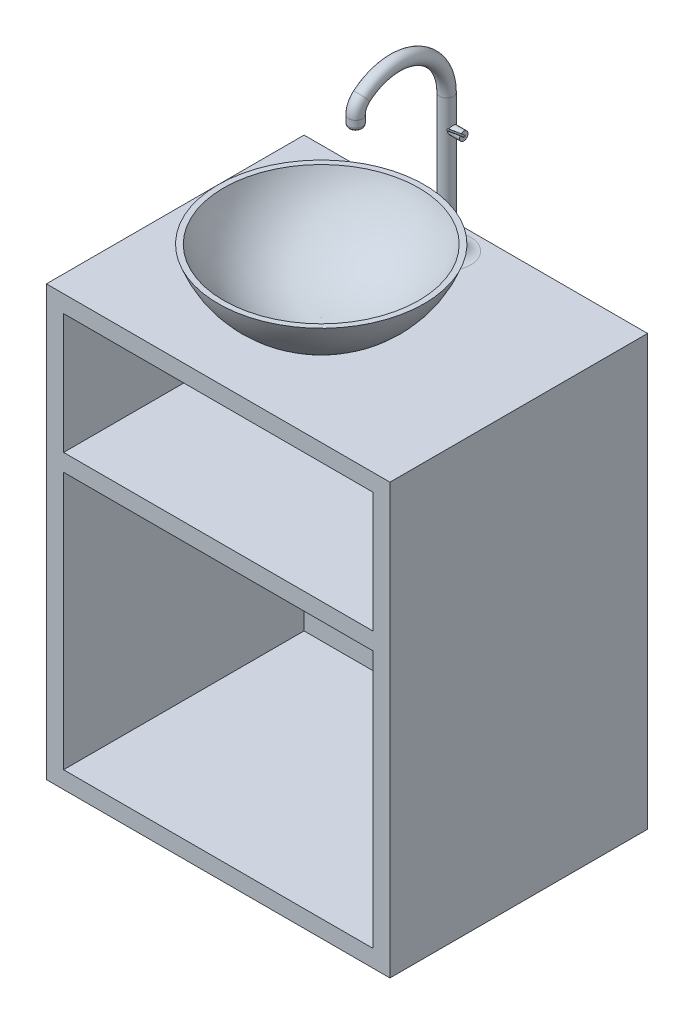
SolidWorks part; units mm, degrees
ref_plane "前基準面" through (0, 0, 0) normal (0, 0, 1) x (1, 0, 0)
ref_plane "上基準面" through (0, 0, 0) normal (0, 1, 0) x (1, 0, 0)
ref_plane "右基準面" through (0, 0, 0) normal (1, 0, 0) x (0, 0, -1)
sketch "草圖1" plane through (0, 0, 0) normal (0, 0, 1) x (1, 0, 0)
  line L1 (-10, 12.5) -> (10, 12.5)
  line L2 (-10, 12.5) -> (-10, -12.5)
  line L3 (-10, -12.5) -> (10, -12.5)
  line L4 (10, 12.5) -> (10, -12.5)
  line L5 (-10, 12.5) -> (10, -12.5) construction
  line L6 (-10, -12.5) -> (10, 12.5) construction
  point P0 (0, 0)
  dimension "D1" = 25
  dimension "D2" = 20
extrude "填料-伸長1" add sketch "草圖1" along normal blind 15
sketch "草圖2" plane through (0, 0, 15) normal (0, 0, 1) x (1, 0, 0)
  line L0 (0, -12.5) -> (0, 12.5) construction
  line L1 (-10, -12.5) -> (10, -12.5) construction
  line L2 (10, 12.5) -> (-10, 12.5) construction
  line L3 (10, -12.5) -> (10, 12.5) construction
  line L4 (-9, 11.5) -> (9, 11.5)
  line L5 (-9, 11.5) -> (-9, 4.5)
  line L6 (-9, 4.5) -> (9, 4.5)
  line L7 (9, 11.5) -> (9, 4.5)
  line L8 (-9, 11.5) -> (9, 4.5) construction
  line L9 (-9, 4.5) -> (9, 11.5) construction
  line L10 (-9, 3.5) -> (9, 3.5)
  line L11 (-9, 3.5) -> (-9, -11.5)
  line L12 (-9, -11.5) -> (9, -11.5)
  line L13 (9, 3.5) -> (9, -11.5)
  line L14 (-9, 3.5) -> (9, -11.5) construction
  line L15 (-9, -11.5) -> (9, 3.5) construction
  point P6 (0, 8)
  point P11 (0, -4)
  dimension "D1" = 1
  dimension "D2" = 1
  dimension "D3" = 1
  dimension "D4" = 1
  dimension "D5" = 1
  dimension "D6" = 15
extrude "除料-伸長1" cut sketch "草圖2" against normal blind 14
ref_plane "平面1" through (0, 0, 0) normal (1, 0, 0) x (0, 0, -1)
sketch "草圖4" plane through (0, 0, 0) normal (1, 0, 0) x (0, 0, -1)
  line L0 (-9, -12.5) -> (-9, 31.1641) construction
  line L1 (-15, -12.5) -> (0, -12.5) construction
  line L2 (-15, -12.5) -> (-15, 12.5) construction
  line L3 (-26.1513, 16.5) -> (9.27, 16.5) construction
  line L4 (-15, 12.5) -> (0, 12.5) construction
  line L5 (-15, 16.5) -> (-14.681, 16.5)
  line L7 (-9.017, 12.7995) -> (-9, 12.7995)
  line L8 (-9, 12.7995) -> (-9, 12.5)
  arc A0 (-15, 16.5) -> (-9, 12.5) centre (-9.3398, 18.4904) ccw
  arc A1 (-14.681, 16.5) -> (-9.017, 12.7995) centre (-9.3398, 18.4904) ccw
  arc A2 (-14.717, 16.5995) -> (-9.017, 12.7995) centre (-9.3398, 18.4904) ccw construction
  dimension "D3" = 6
  dimension "D1" = 6
  dimension "D2" = 4
  dimension "D4" = 4
  dimension "D5" = 6
  dimension "D6" = 0.3
revolve "旋轉4" add sketch "草圖4" angle 360 about L0
sketch "草圖5" plane through (0, 12.5, 0) normal (0, 1, 0) x (1, 0, 0)
  line L0 (10, 0) -> (-10, 0) construction
  line L1 (-10, -15) -> (-10, 0) construction
  circle A0 centre (0, -1.7) radius 0.4
  dimension "D1" = 0.8
  dimension "D2" = 1.7
  dimension "D3" = 10
sketch "草圖6" plane through (0, 0, 0) normal (1, 0, 0) x (0, 0, -1)
  line L0 (-1.7, 12.5) -> (-1.7, 20.5)
  line L1 (-1.3, 12.5) -> (-2.1, 12.5) construction
  line L2 (-6.9981, 22.0215) -> (-6.9981, 21.4284)
  line L3 (-6.9981, 22.4284) -> (-4.7, 20.5) construction
  line L4 (-4.7, 20.5) -> (-1.7, 20.5) construction
  arc A0 (-1.7, 20.5) -> (-6.6472, 22.7822) centre (-4.7, 20.5) ccw
  arc A1 (-6.6472, 22.7822) -> (-6.9981, 22.0215) centre (-5.9981, 22.0215) ccw
  dimension "D2" = 3
  dimension "D5" = 1
  dimension "D1" = 8
  dimension "D3" = 1
  dimension "D4" = 220
sweep "掃出1" add profiles "草圖5" path "草圖6"
fillet "圓角1" radius 1 1 edges at (0, 12.5, 2.1)
sketch "草圖7" plane through (0, 0, 0) normal (1, 0, 0) x (0, 0, -1)
  line L0 (-1.7, 13.5) -> (-1.7, 20.5) construction
  line L1 (-1.3, 13.5) -> (-2.1, 13.5) construction
  line L2 (-2.1, 20.5) -> (-1.3, 20.5) construction
  line L3 (-15, 12.5) -> (0, 12.5) construction
  circle A0 centre (-1.7, 18.8) radius 0.25
  dimension "D1" = 0.5
  dimension "D2" = 6.3
extrude "填料-伸長3" add sketch "草圖7" along normal blind 1
sketch "草圖8" plane through (1, 0, 0) normal (1, 0, 0) x (0, 0, -1)
  line L0 (-1.7, 18.8) -> (-2.6193, 19.5713) construction
  line L1 (-2.1, 20.5) -> (-2.1, 13.5) construction
  line L2 (-2.6193, 19.5713) -> (-1.7, 18.8)
  line L3 (-2.6193, 19.5713) -> (-2.6514, 19.533)
  line L4 (-1.7, 18.8) -> (-1.7321, 18.7617)
  line L5 (-2.6514, 19.533) -> (-1.7321, 18.7617)
  line L6 (-1.7, 18.8) -> (-0.5155, 17.8061) construction
  dimension "D1" = 50
  dimension "D2" = 0.05
  dimension "D3" = 1.2
revolve "旋轉5" add sketch "草圖8" angle 360 about L6
fillet "圓角2" radius 0.2 1 edges at (0, 21.4284, 6.5981)
equation "\"ㄉ5\"=10"
